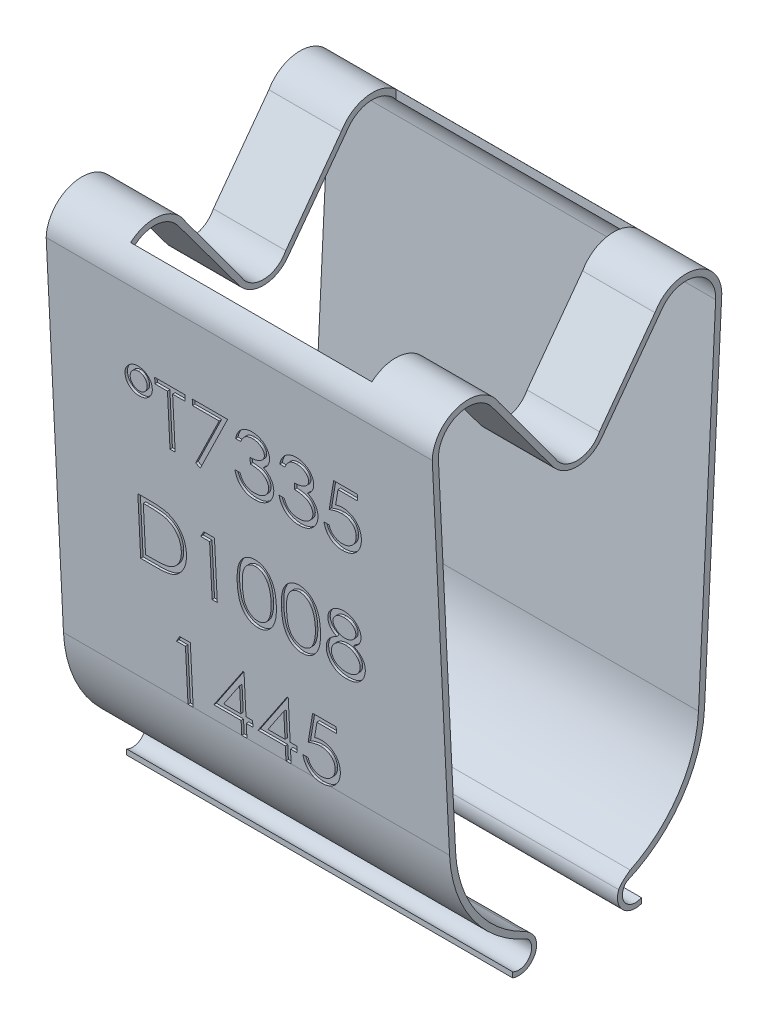
SolidWorks part; units mm, degrees
ref_plane "Front Plane" through (0, 0, 0) normal (0, 0, 1) x (1, 0, 0)
ref_plane "Top Plane" through (0, 0, 0) normal (0, 1, 0) x (1, 0, 0)
ref_plane "Right Plane" through (0, 0, 0) normal (1, 0, 0) x (0, 0, -1)
sketch "Sketch1" plane through (0, 0, 0) normal (1, 0, 0) x (0, 0, -1)
  line L1 (-5.2836, -0.2605) -> (-6, 14.2712)
  line L2 (5.2836, -0.2605) -> (6, 14.2712)
  line L3 (-5.0339, -0.2482) -> (-5.7446, 14.1685)
  line L4 (5.0339, -0.2482) -> (5.7446, 14.1685)
  line L5 (-2.6647, -5.7524) -> (-2.6647, -5.9731)
  line L6 (2.6647, -5.7524) -> (2.6647, -5.9731)
  line L7 (3.5328, 14.9602) -> (1.0086, 11.5569)
  line L8 (3.2293, 14.9594) -> (0.9298, 11.8366)
  line L9 (-3.2293, 14.9594) -> (-0.9298, 11.8366)
  line L10 (-3.5328, 14.9602) -> (-1.0086, 11.5569)
  arc A0 (-5.0339, -0.2482) -> (-2.2046, -4.5323) centre (0, 0) ccw
  arc A1 (-5.2836, -0.2605) -> (-2.0522, -4.8757) centre (0, 0) ccw
  arc A2 (-2.0522, -4.8757) -> (-2.6647, -5.7524) centre (-2.4185, -5.2721) cw
  arc A3 (-2.6647, -5.9731) -> (-1.7271, -5.0001) centre (-2.4185, -5.2721) ccw
  arc A4 (2.2046, -4.5323) -> (5.0339, -0.2482) centre (0, 0) ccw
  arc A5 (2.0522, -4.8757) -> (2.6647, -5.7524) centre (2.4185, -5.2721) ccw
  arc A6 (2.6647, -5.9731) -> (1.7271, -5.0001) centre (2.4185, -5.2721) cw
  arc A7 (2.0522, -4.8757) -> (5.2836, -0.2605) centre (0, 0) ccw
  arc A8 (5.7446, 14.1685) -> (3.5328, 14.9602) centre (4.5187, 14.229) ccw
  arc A9 (6, 14.2712) -> (3.2293, 14.9594) centre (4.5187, 14.229) ccw
  arc A12 (-1.0086, 11.5569) -> (1.0086, 11.5569) centre (0, 12.305) ccw
  arc A13 (-0.9298, 11.8366) -> (0.9298, 11.8366) centre (0, 12.305) ccw
  arc A14 (-6, 14.2712) -> (-3.2293, 14.9594) centre (-4.5187, 14.229) cw
  arc A15 (-5.7446, 14.1685) -> (-3.5328, 14.9602) centre (-4.5187, 14.229) cw
  spline S0 degree 3 poles (-1.7271, -5.0001) (-1.7843, -4.8447) (-2.0196, -4.6157) (-2.2046, -4.5323) knots 0 0 0 0 1 1 1 1
  spline S1 degree 3 poles (1.7271, -5.0001) (1.7836, -4.8445) (2.0373, -4.6472) (2.2046, -4.5323) knots 0 0 0 0 1 1 1 1
extrude "Boss-Extrude1" add sketch "Sketch1" along normal blind 16
sketch3d "3DSketch1"
  point P0 (9.1988, 11.2716, 0.1262)
ref_plane "Plane1" through (0, 11.2716, 0) normal (0, 1, 0) x (0, 0, 1)
sketch "Sketch2" plane through (0, 11.2716, 0) normal (0, 1, 0) x (0, 0, 1)
  line L0 (-6, 16) -> (6, 0) construction
  line L1 (6, 0) -> (6, 16) construction
  line L2 (6, 16) -> (-6, 0) construction
  line L4 (-5.5, 13) -> (5.5, 13)
  line L5 (-5.5, 13) -> (-5.5, 3)
  line L6 (-5.5, 3) -> (5.5, 3)
  line L7 (5.5, 13) -> (5.5, 3)
  line L8 (-5.5, 13) -> (5.5, 3) construction
  line L9 (-5.5, 3) -> (5.5, 13) construction
  point P4 (0, 8)
  dimension "D1" = 11
  dimension "D2" = 10
extrude "Cut-Extrude1" cut sketch "Sketch2" against normal blind 1 and the other way blind 10
sketch "Sketch4" plane through (0, -0.2605, 5.2836) normal (0, -0.0492, 0.9988) x (1, 0, 0)
  line L1 (0, 9.2525) -> (16, 9.2525) construction
  line L2 (0, 14.5493) -> (0, 0) construction
  line L3 (16, 14.5493) -> (16, 0) construction
  line L4 (16, 9.2525) -> (16, 4.4859) construction
  line L5 (16, 4.4859) -> (0, 4.4859) construction
  line L6 (0, 4.4859) -> (0, 0) construction
  line L7 (0, 0) -> (16, 0) construction
  text T0 "°T7335\r\n" font "Century Gothic" height in points 9
  text T1 "D1008\r\n" font "Century Gothic" height in points 9
  text T2 "1445" font "Century Gothic" height in points 9
extrude "Cut-Extrude3" cut sketch "Sketch4" against normal blind 0.1
